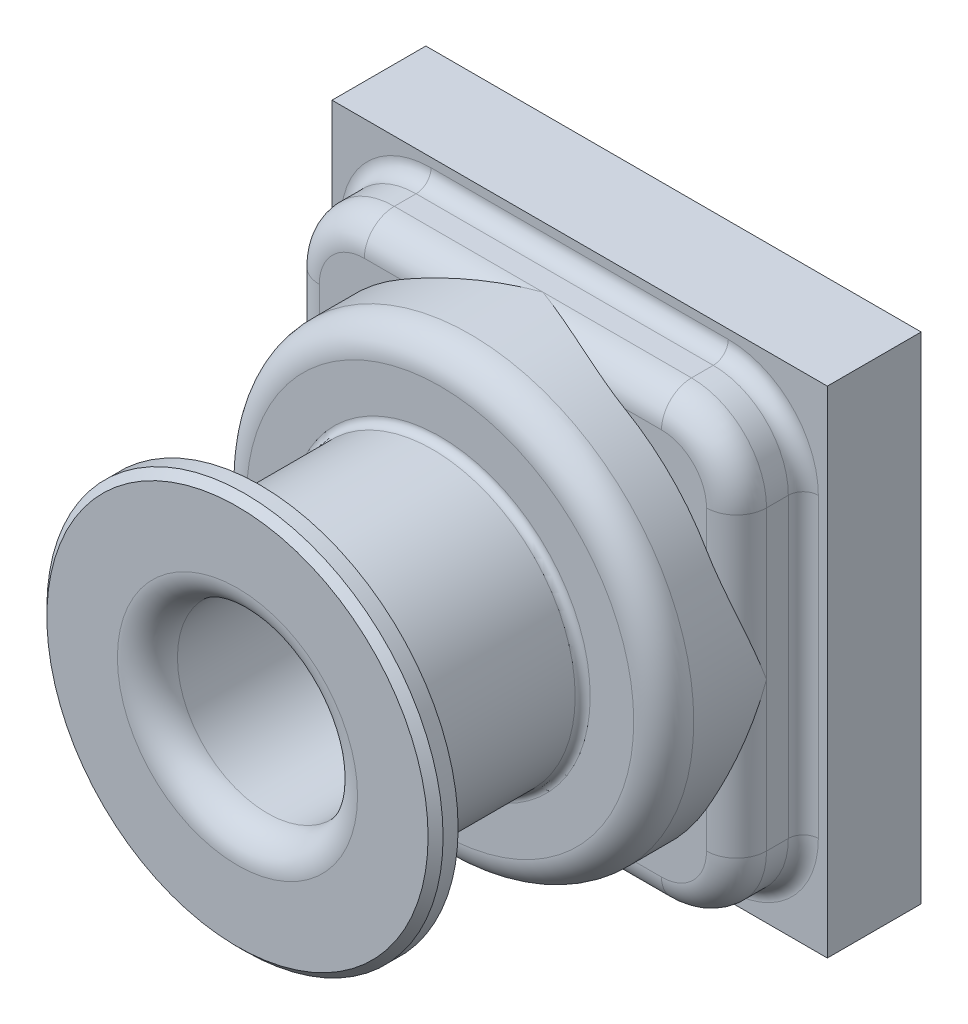
SolidWorks part; units mm, degrees
ref_plane "Plan de face" through (0, 0, 0) normal (0, 0, 1) x (1, 0, 0)
ref_plane "Plan de dessus" through (0, 0, 0) normal (0, 1, 0) x (1, 0, 0)
ref_plane "Plan de droite" through (0, 0, 0) normal (1, 0, 0) x (0, 0, -1)
sketch "Esquisse1" plane through (0, 0, 0) normal (0, 0, 1) x (1, 0, 0)
  line L1 (-1.65, 1.65) -> (1.65, 1.65)
  line L2 (-1.65, 1.65) -> (-1.65, -1.65)
  line L3 (-1.65, -1.65) -> (1.65, -1.65)
  line L4 (1.65, 1.65) -> (1.65, -1.65)
  line L5 (-1.65, 1.65) -> (1.65, -1.65) construction
  line L6 (-1.65, -1.65) -> (1.65, 1.65) construction
  point P0 (0, 0)
  dimension "D1" = 3.3
extrude "base" add sketch "Esquisse1" along normal blind 0.625
sketch "Esquisse2" plane through (0, 0, 0.625) normal (0, 0, 1) x (1, 0, 0)
  line L1 (-0.99, 1.49) -> (0.99, 1.49)
  line L2 (-1.49, 0.99) -> (-1.49, -0.99)
  line L3 (-0.99, -1.49) -> (0.99, -1.49)
  line L4 (1.49, 0.99) -> (1.49, -0.99)
  line L5 (-1.49, 1.49) -> (1.49, -1.49) construction
  line L6 (-1.49, -1.49) -> (1.49, 1.49) construction
  arc A0 (-1.49, -0.99) -> (-0.99, -1.49) centre (-0.99, -0.99) ccw
  arc A1 (0.99, -1.49) -> (1.49, -0.99) centre (0.99, -0.99) ccw
  arc A2 (1.49, 0.99) -> (0.99, 1.49) centre (0.99, 0.99) ccw
  arc A3 (-0.99, 1.49) -> (-1.49, 0.99) centre (-0.99, 0.99) ccw
  point P0 (0, 0)
  dimension "D1" = 0.5
  dimension "D2" = 0.5
  dimension "D3" = 2.98
extrude "Boss.-Extru.2" add sketch "Esquisse2" along normal blind 0.445
fillet "Congé1" radius 0.2 8 edges at (1.3436, -1.3436, 1.07) (0, -1.49, 1.07) (-1.3436, -1.3436, 1.07) (-1.49, 0, 1.07) (-1.3436, 1.3436, 1.07) (0, 1.49, 1.07) (1.3436, 1.3436, 1.07) (1.49, 0, 1.07)
sketch "Esquisse3" plane through (0, 0, 0.625) normal (0, 0, 1) x (1, 0, 0)
  line L0 (1.49, -0.99) -> (1.49, 0.99) construction
  circle A0 centre (0, 0) radius 1.49
extrude "Boss.-Extru.3" add sketch "Esquisse3" along normal blind 0.93
fillet "Congé2" radius 0.1 8 edges at (-1.3436, -1.3436, 0.625) (-1.49, 0, 0.625) (-1.3436, 1.3436, 0.625) (0, 1.49, 0.625) (1.3436, 1.3436, 0.625) (1.49, 0, 0.625) (1.3436, -1.3436, 0.625) (0, -1.49, 0.625)
sketch "Esquisse4" plane through (0, 0, 1.555) normal (0, 0, 1) x (1, 0, 0)
  circle A0 centre (0, 0) radius 0.95
  circle A1 centre (0, 0) radius 0.6
  dimension "D1" = 1.9
  dimension "D2" = 1.2
extrude "Boss.-Extru.4" add sketch "Esquisse4" along normal blind 1.2
sketch "Esquisse6" plane through (0, 0, 2.755) normal (0, 0, 1) x (1, 0, 0)
  circle A0 centre (0, 0) radius 0.6 construction
  circle A1 centre (0, 0) radius 0.6
  circle A2 centre (0, 0) radius 1.32
  dimension "D1" = 2.64
extrude "Boss.-Extru.5" add sketch "Esquisse6" along normal blind 0.15
chamfer "Chanfrein1" distance 0.05 angle 45 1 edges at (1.32, 0, 2.905)
fillet "Congé3" radius 0.05 2 edges at (0.95, 0, 1.555) (0.95, 0, 2.755)
fillet "Congé4" radius 0.2 2 edges at (1.49, 0, 1.555) (0.6, 0, 2.905)
